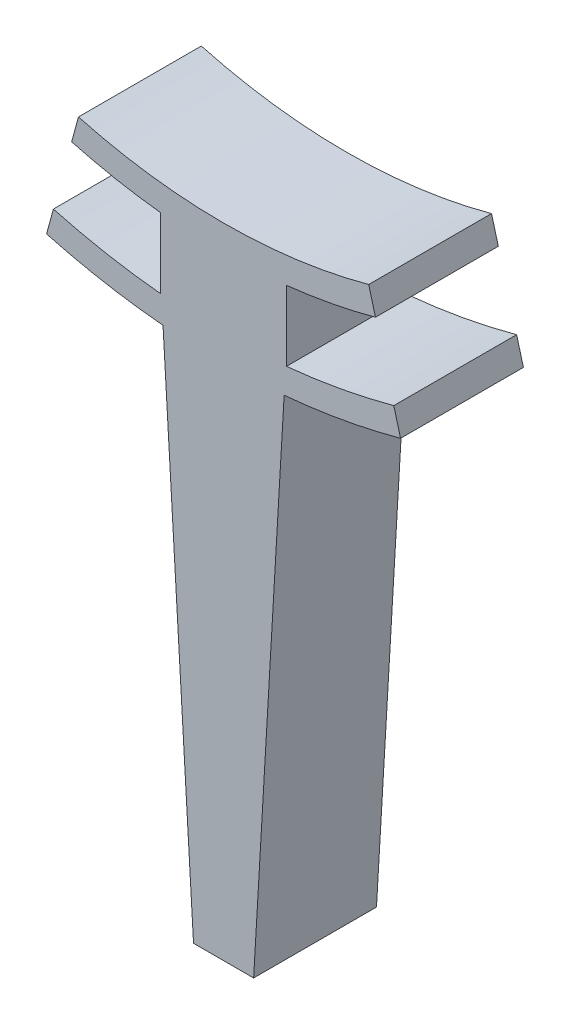
SolidWorks part; units mm, degrees
ref_plane "Front Plane" through (0, 0, 0) normal (0, 0, 1) x (1, 0, 0)
ref_plane "Top Plane" through (0, 0, 0) normal (0, 1, 0) x (1, 0, 0)
ref_plane "Right Plane" through (0, 0, 0) normal (1, 0, 0) x (0, 0, -1)
sketch "Sketch1" plane through (0, 0, 0) normal (0, 0, 1) x (1, 0, 0)
  line L0 (-50.3, 16.86) -> (49.7, 16.86) construction
  line L1 (-5.1652, -27.675) -> (-5.1652, -33.1037)
  line L2 (-0.3, -28.1891) -> (-0.3, -50028.1891) construction
  line L3 (-13.4635, -31.5834) -> (-13.988, -33.5134)
  line L4 (-12.0475, -26.3723) -> (-11.5231, -24.4423)
  line L5 (-4.9836, -35.1295) -> (-2.6244, -75.34)
  line L6 (-2.6244, -75.34) -> (2.0244, -75.34)
  line L7 (4.3836, -35.1295) -> (2.0244, -75.34)
  line L8 (12.8635, -31.5834) -> (13.388, -33.5134)
  line L9 (4.5652, -27.675) -> (4.5652, -33.1037)
  line L10 (11.4475, -26.3723) -> (10.9231, -24.4423)
  line L11 (4.7652, -32.8828) -> (4.7652, -27.854) construction
  arc A0 (-45.9111, 37.3448) -> (-5.2348, -32.8959) centre (-0.3, 16.86) ccw construction
  arc A1 (4.7652, -32.8828) -> (45.2573, 37.4642) centre (-0.3, 16.86) ccw construction
  arc A2 (-5.2348, -32.8959) -> (4.7652, -32.8828) centre (-0.3, 16.86) ccw construction
  arc A13 (-12.0475, -26.3723) -> (-5.1652, -27.675) centre (-0.3, 16.86) ccw
  arc A17 (-11.5231, -24.4423) -> (10.9231, -24.4423) centre (-0.3, 16.86) ccw
  arc A18 (-13.4635, -31.5834) -> (-5.1652, -33.1037) centre (-0.3, 16.86) ccw
  arc A19 (-13.988, -33.5134) -> (-4.9836, -35.1295) centre (-0.3, 16.86) ccw
  arc A21 (4.7652, -27.854) -> (40.9035, 34.9506) centre (-0.3, 16.86) ccw construction
  arc A22 (44.5, 16.86) -> (-45.1, 16.86) centre (-0.3, 16.86) ccw
  arc A23 (42.5, 16.86) -> (-43.1, 16.86) centre (-0.3, 16.86) ccw
  arc A24 (4.5652, -27.675) -> (11.4475, -26.3723) centre (-0.3, 16.86) ccw
  arc A25 (4.5652, -33.1037) -> (12.8635, -31.5834) centre (-0.3, 16.86) ccw
  arc A26 (4.3836, -35.1295) -> (13.388, -33.5134) centre (-0.3, 16.86) ccw
  point P38 (-0.3, -35.34)
  point P39 (-0.3, -75.34)
  dimension "D1" = 0.2
  dimension "D2" = 0.2
  dimension "D3" = 2
  dimension "D4" = 2
  dimension "D5" = 40
  dimension "D6" = 0.2
extrude "Boss-Extrude1" add sketch "Sketch1" against normal blind 9.5 contours L3 A19 L5 L6 L7 A26 L8 A25 L9 A24 L10 A17 L4 A13 L1 A18
equation "\".`\"=0.5"
